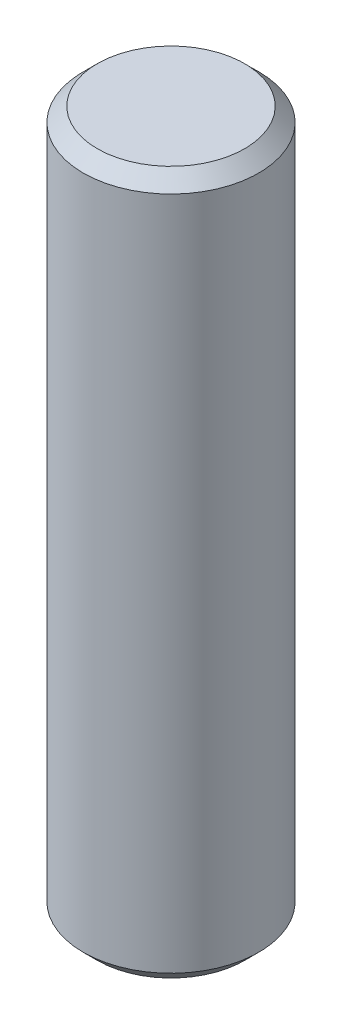
SolidWorks part; units mm, degrees
ref_plane "Front Plane" through (0, 0, 0) normal (0, 0, 1) x (1, 0, 0)
ref_plane "Top Plane" through (0, 0, 0) normal (0, 1, 0) x (1, 0, 0)
ref_plane "Right Plane" through (0, 0, 0) normal (1, 0, 0) x (0, 0, -1)
ref_plane "Plane1" through (0, 0, 0) normal (0, 0, -1) x (-1, 0, 0)
sketch "Sketch1" plane through (0, 0, 0) normal (0, 0, -1) x (-1, 0, 0)
  line L0 (-2.6632, 0) -> (0, 0)
  line L1 (0, 0) -> (0, 25.4)
  line L2 (0, 25.4) -> (-2.6632, 25.4)
  line L3 (-2.6632, 25.4) -> (-3.1712, 24.892)
  line L4 (-3.1712, 24.892) -> (-3.1712, 0.508)
  line L5 (-3.1712, 0.508) -> (-2.6632, 0)
  line L6 (0, 0) -> (0, 25.4) construction
revolve "Revolve1" add sketch "Sketch1" angle 360 about L6
